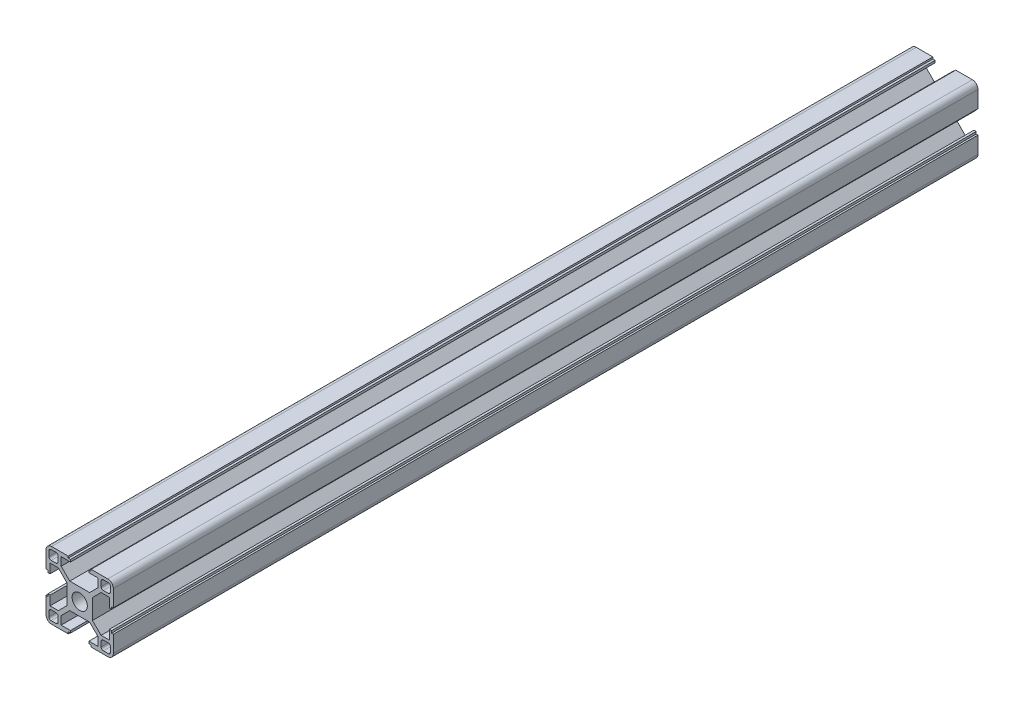
SolidWorks part; units mm, degrees
material "6061-T6 (SS)"
ref_plane "前视基准面" through (0, 0, 0) normal (0, 0, 1) x (1, 0, 0)
ref_plane "上视基准面" through (0, 0, 0) normal (0, 1, 0) x (1, 0, 0)
ref_plane "右视基准面" through (0, 0, 0) normal (1, 0, 0) x (0, 0, -1)
sketch "Sketch1" plane through (0, 0, 0) normal (0, 0, 1) x (1, 0, 0)
  line L0 (-5.1, 15) -> (-5.1, 14.2)
  line L1 (-12.5, -15) -> (12.5, -15)
  line L2 (-15, -12.5) -> (-15, 12.5)
  line L3 (-12.5, 15) -> (12.5, 15)
  line L4 (15, -12.5) -> (15, 12.5)
  line L5 (-15, -15) -> (15, 15) construction
  line L6 (-15, 15) -> (15, -15) construction
  line L7 (-5.1, 14.2) -> (-4.1, 14.2)
  line L8 (-4.1, 14.2) -> (-4.1, 13.2)
  line L9 (-4.1, 13.2) -> (-8.25, 13.2)
  line L10 (-8.25, 13.2) -> (-8.25, 9.5228)
  line L11 (-8.25, 9.5228) -> (-4.4272, 5.7)
  line L12 (-4.4272, 5.7) -> (4.4272, 5.7)
  line L13 (-5.1, 15) -> (5.1, 15)
  line L14 (0, 15) -> (0, 5.7) construction
  line L15 (8.25, 9.5228) -> (4.4272, 5.7)
  line L16 (8.25, 13.2) -> (8.25, 9.5228)
  line L17 (4.1, 13.2) -> (8.25, 13.2)
  line L18 (4.1, 14.2) -> (4.1, 13.2)
  line L19 (5.1, 14.2) -> (4.1, 14.2)
  line L20 (5.1, 15) -> (5.1, 14.2)
  line L21 (15, 5.1) -> (14.2, 5.1)
  line L22 (14.2, 5.1) -> (14.2, 4.1)
  line L23 (14.2, 4.1) -> (13.2, 4.1)
  line L24 (13.2, 4.1) -> (13.2, 8.25)
  line L25 (13.2, 8.25) -> (9.5228, 8.25)
  line L26 (9.5228, 8.25) -> (5.7, 4.4272)
  line L27 (5.7, 4.4272) -> (5.7, -4.4272)
  line L28 (15, 5.1) -> (15, -5.1)
  line L29 (9.5228, -8.25) -> (5.7, -4.4272)
  line L30 (13.2, -8.25) -> (9.5228, -8.25)
  line L31 (13.2, -4.1) -> (13.2, -8.25)
  line L32 (14.2, -4.1) -> (13.2, -4.1)
  line L33 (14.2, -5.1) -> (14.2, -4.1)
  line L34 (15, -5.1) -> (14.2, -5.1)
  line L35 (15, 0) -> (5.7, 0) construction
  line L36 (5.1, -15) -> (5.1, -14.2)
  line L37 (5.1, -14.2) -> (4.1, -14.2)
  line L38 (4.1, -14.2) -> (4.1, -13.2)
  line L39 (4.1, -13.2) -> (8.25, -13.2)
  line L40 (8.25, -13.2) -> (8.25, -9.5228)
  line L41 (8.25, -9.5228) -> (4.4272, -5.7)
  line L42 (4.4272, -5.7) -> (-4.4272, -5.7)
  line L43 (5.1, -15) -> (-5.1, -15)
  line L44 (-8.25, -9.5228) -> (-4.4272, -5.7)
  line L45 (-8.25, -13.2) -> (-8.25, -9.5228)
  line L46 (-4.1, -13.2) -> (-8.25, -13.2)
  line L47 (-4.1, -14.2) -> (-4.1, -13.2)
  line L48 (-5.1, -14.2) -> (-4.1, -14.2)
  line L49 (-5.1, -15) -> (-5.1, -14.2)
  line L50 (0, -15) -> (0, -5.7) construction
  line L51 (-15, -5.1) -> (-14.2, -5.1)
  line L52 (-14.2, -5.1) -> (-14.2, -4.1)
  line L53 (-14.2, -4.1) -> (-13.2, -4.1)
  line L54 (-13.2, -4.1) -> (-13.2, -8.25)
  line L55 (-13.2, -8.25) -> (-9.5228, -8.25)
  line L56 (-9.5228, -8.25) -> (-5.7, -4.4272)
  line L57 (-5.7, -4.4272) -> (-5.7, 4.4272)
  line L58 (-15, -5.1) -> (-15, 5.1)
  line L59 (-9.5228, 8.25) -> (-5.7, 4.4272)
  line L60 (-13.2, 8.25) -> (-9.5228, 8.25)
  line L61 (-13.2, 4.1) -> (-13.2, 8.25)
  line L62 (-14.2, 4.1) -> (-13.2, 4.1)
  line L63 (-14.2, 5.1) -> (-14.2, 4.1)
  line L64 (-15, 5.1) -> (-14.2, 5.1)
  line L65 (-15, 0) -> (-5.7, 0) construction
  line L66 (0, 0) -> (0, 5.7) construction
  circle A0 centre (0, 0) radius 3.4
  arc A1 (-12.5, -15) -> (-15, -12.5) centre (-12.5, -12.5) cw
  arc A2 (12.5, -15) -> (15, -12.5) centre (12.5, -12.5) ccw
  arc A3 (12.5, 15) -> (15, 12.5) centre (12.5, 12.5) cw
  arc A4 (-15, 12.5) -> (-12.5, 15) centre (-12.5, 12.5) cw
  point P0 (0, 0)
  dimension "D3" = 6.8
  dimension "D12" = 2.5
  dimension "D1" = 30
  dimension "D2" = 30
  dimension "D4" = 16.5
  dimension "D5" = 8.2
  dimension "D6" = 10.2
  dimension "D7" = 7.5
  dimension "D9" = 1.8
  dimension "D10" = 1.8
  dimension "D11" = 0.8
  dimension "D8" = 4
extrude "Extrude1" add sketch "Sketch1" along normal blind 385 contours A4 L2 L64 L63 L62 L61 L60 L59 L57 L56 L55 L54 L53 L52 L51 A1 L1 L49 L48 L47 L46 L45 L44 L42 L41 L40 L39 L38 L37 L36 A2 L4 L34 L33 L32 L31 L30 L29 L27 L26 L25 L24 L23 L22 L21 A3 L3 L20
sketch "Sketch2" plane through (0, 0, 385) normal (0, 0, 1) x (1, 0, 0)
  line L0 (13.7, 12.7) -> (13.7, 10.55)
  line L1 (-12.7, 13.7) -> (-10.55, 13.7)
  line L2 (-13.7, 12.7) -> (-13.7, 10.55)
  line L3 (-12.7, 9.55) -> (-10.55, 9.55)
  line L4 (-9.55, 12.7) -> (-9.55, 10.55)
  line L5 (-13.7, 13.7) -> (-9.55, 9.55) construction
  line L6 (-13.7, 9.55) -> (-9.55, 13.7) construction
  line L7 (12.7, 13.7) -> (10.55, 13.7)
  line L8 (9.55, 12.7) -> (9.55, 10.55)
  line L9 (12.7, 9.55) -> (10.55, 9.55)
  line L10 (12.7, -13.7) -> (10.55, -13.7)
  line L11 (13.7, -12.7) -> (13.7, -10.55)
  line L12 (12.7, -9.55) -> (10.55, -9.55)
  line L13 (9.55, -12.7) -> (9.55, -10.55)
  line L14 (-13.7, -12.7) -> (-13.7, -10.55)
  line L15 (-12.7, -13.7) -> (-10.55, -13.7)
  line L16 (-9.55, -12.7) -> (-9.55, -10.55)
  line L17 (-12.7, -9.55) -> (-10.55, -9.55)
  line L18 (0, 0) -> (-9.55, 9.55) construction
  line L19 (-12.5, 15) -> (-5.1, 15) construction
  line L20 (-15, 5.1) -> (-15, 12.5) construction
  line L21 (-13.2, 8.25) -> (-9.5228, 8.25) construction
  line L22 (-8.25, 13.2) -> (-8.25, 9.5228) construction
  arc A0 (-13.7, -12.7) -> (-12.7, -13.7) centre (-12.7, -12.7) ccw
  arc A1 (-10.55, -13.7) -> (-9.55, -12.7) centre (-10.55, -12.7) ccw
  arc A2 (-9.55, -10.55) -> (-10.55, -9.55) centre (-10.55, -10.55) ccw
  arc A3 (-13.7, -10.55) -> (-12.7, -9.55) centre (-12.7, -10.55) cw
  arc A4 (13.7, -10.55) -> (12.7, -9.55) centre (12.7, -10.55) ccw
  arc A5 (12.7, -13.7) -> (13.7, -12.7) centre (12.7, -12.7) ccw
  arc A6 (10.55, -13.7) -> (9.55, -12.7) centre (10.55, -12.7) cw
  arc A7 (10.55, -9.55) -> (9.55, -10.55) centre (10.55, -10.55) ccw
  arc A8 (13.7, 12.7) -> (12.7, 13.7) centre (12.7, 12.7) ccw
  arc A9 (13.7, 10.55) -> (12.7, 9.55) centre (12.7, 10.55) cw
  arc A10 (9.55, 10.55) -> (10.55, 9.55) centre (10.55, 10.55) ccw
  arc A11 (10.55, 13.7) -> (9.55, 12.7) centre (10.55, 12.7) ccw
  arc A12 (-10.55, 13.7) -> (-9.55, 12.7) centre (-10.55, 12.7) cw
  arc A13 (-10.55, 9.55) -> (-9.55, 10.55) centre (-10.55, 10.55) ccw
  arc A14 (-13.7, 10.55) -> (-12.7, 9.55) centre (-12.7, 10.55) ccw
  arc A15 (-12.7, 13.7) -> (-13.7, 12.7) centre (-12.7, 12.7) ccw
  point P0 (-11.625, 11.625)
  dimension "D2" = 1
  dimension "D3" = 1.3
  dimension "D4" = 1.3
  dimension "D5" = 1.3
  dimension "D6" = 1.3
  dimension "D1" = 4
extrude "Extrude2" cut sketch "Sketch2" against normal through all
